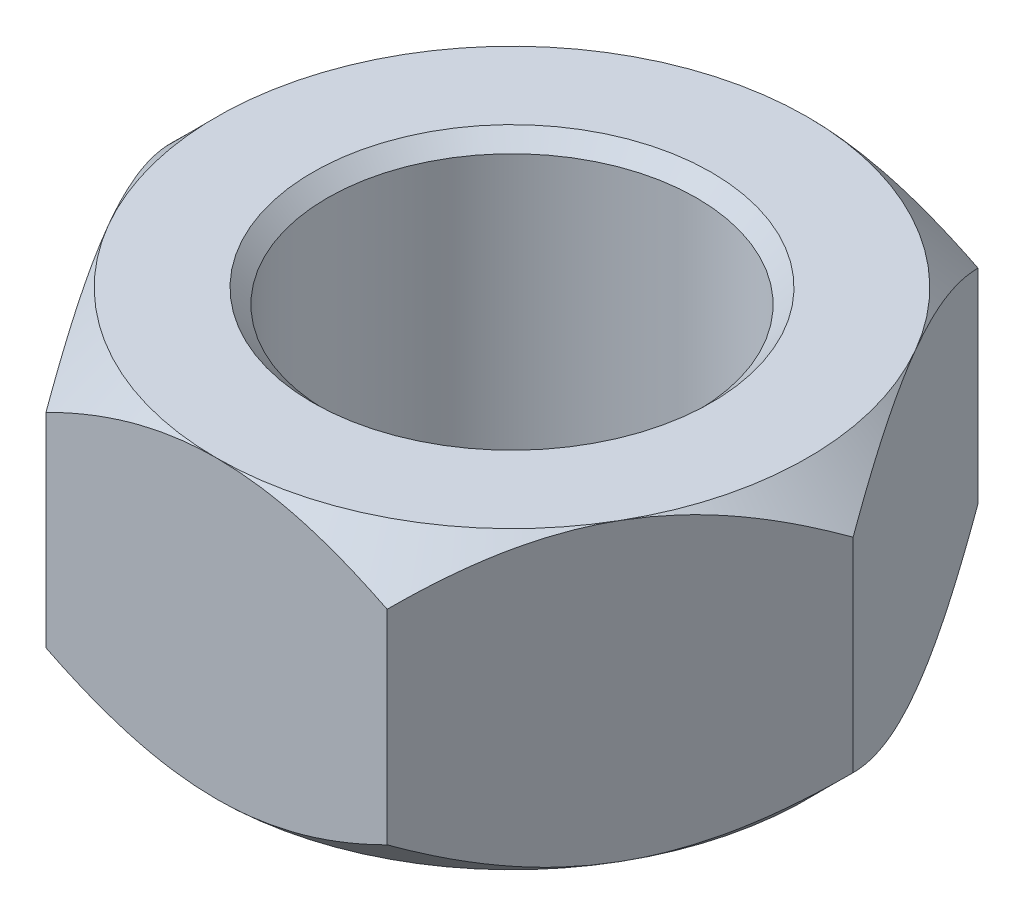
SolidWorks part; units mm, degrees
ref_plane "Front Plane" through (0, 0, 0) normal (0, 0, 1) x (1, 0, 0)
ref_plane "Top Plane" through (0, 0, 0) normal (0, 1, 0) x (1, 0, 0)
ref_plane "Right Plane" through (0, 0, 0) normal (1, 0, 0) x (0, 0, -1)
sketch "Sketch1" plane through (0, 0, 0) normal (0, 1, 0) x (1, 0, 0)
  line L1 (-2.3094, 4) -> (-4.6188, 0)
  line L2 (-4.6188, 0) -> (-2.3094, -4)
  line L3 (-2.3094, -4) -> (2.3094, -4)
  line L4 (2.3094, -4) -> (4.6188, 0)
  line L5 (4.6188, 0) -> (2.3094, 4)
  line L6 (2.3094, 4) -> (-2.3094, 4)
  circle A0 centre (0, 0) radius 4 construction
  circle A1 centre (0, 0) radius 2.5
  dimension "D1" = 5
  dimension "D2" = 8
extrude "Boss-Extrude1" add sketch "Sketch1" along normal blind 4
chamfer "Chamfer1" distance 0.2 angle 45 2 edges at (0, 0, 2.5) (0, 4, 2.5)
sketch "Sketch2" plane through (0, 0, 0) normal (0, 0, 1) x (1, 0, 0)
  line L0 (0, 0) -> (0, 5.2614) construction
  line L1 (-4, 4) -> (-5, 3)
  line L2 (-5, 3) -> (-5, 4)
  line L3 (-5, 4) -> (-4, 4)
  line L4 (-4.6188, 4) -> (-2.3094, 4) construction
  line L5 (-5.746, 2) -> (5.192, 2) construction
  line L6 (-5, 0) -> (-4, 0)
  line L7 (-5, 1) -> (-5, 0)
  line L8 (-4, 0) -> (-5, 1)
  dimension "D1" = 5
  dimension "D2" = 45
  dimension "D3" = 4
  dimension "D4" = 2
revolve "Cut-Revolve1" cut sketch "Sketch2" angle 360 about L0
